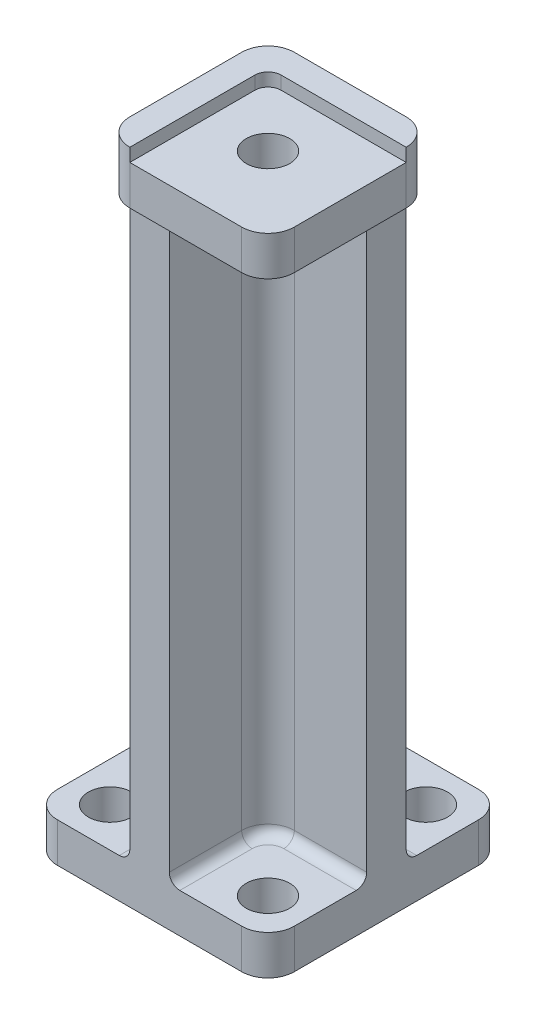
SolidWorks part; units mm, degrees
ref_plane "前视基准面" through (0, 0, 0) normal (0, 0, 1) x (1, 0, 0)
ref_plane "上视基准面" through (0, 0, 0) normal (0, 1, 0) x (1, 0, 0)
ref_plane "右视基准面" through (0, 0, 0) normal (1, 0, 0) x (0, 0, -1)
other "Configuration Table"
sketch "草图1" plane through (0, 0, 0) normal (0, 1, 0) x (1, 0, 0)
  line L1 (-9, 9) -> (9, 9)
  line L2 (-9, 9) -> (-9, -9)
  line L3 (-9, -9) -> (9, -9)
  line L4 (9, 9) -> (9, -9)
  line L5 (-9, 9) -> (9, -9) construction
  line L6 (-9, -9) -> (9, 9) construction
  point P0 (0, 0)
  dimension "D1" = 18
extrude "凸台-拉伸1" add sketch "草图1" along normal blind 3
sketch "草图2" plane through (0, 3, 0) normal (0, 1, 0) x (1, 0, 0)
  line L1 (-6, 6) -> (6, 6) construction
  line L2 (-6, 6) -> (-6, -6) construction
  line L3 (-6, -6) -> (6, -6) construction
  line L4 (6, 6) -> (6, -6) construction
  line L5 (-6, 6) -> (6, -6) construction
  line L6 (-6, -6) -> (6, 6) construction
  circle A0 centre (-6, 6) radius 1.65
  circle A1 centre (6, 6) radius 1.65
  circle A2 centre (6, -6) radius 1.65
  circle A3 centre (-6, -6) radius 1.65
  point P0 (0, 0)
  point P16 (0, 0)
  dimension "D2" = 3.3
  dimension "D1" = 12
  dimension "D3" = 4
extrude "切除-拉伸1" cut sketch "草图2" against normal blind 3
sketch "草图3" plane through (0, 3, 0) normal (0, 1, 0) x (1, 0, 0)
  line L0 (-9, -9) -> (9, -9) construction
  line L1 (-1.5, -9) -> (1.5, -9)
  line L2 (-1.5, -9) -> (-1.5, 1.5)
  line L3 (-1.5, 1.5) -> (1.5, 1.5)
  line L4 (1.5, -9) -> (1.5, 1.5)
  line L5 (9, -9) -> (9, 9) construction
  line L6 (9, -1.5) -> (-1.5, -1.5)
  line L7 (9, -1.5) -> (9, 1.5)
  line L8 (9, 1.5) -> (-1.5, 1.5)
  line L9 (-1.5, -1.5) -> (-1.5, 1.5)
  line L10 (0, 9) -> (0, -9) construction
  line L12 (9, 9) -> (-9, 9) construction
  line L13 (9, 0) -> (-9, 0) construction
  line L14 (-9, 9) -> (-9, -9) construction
  line M16 (9, -9) -> (9, 9)
  line M19 (-9, -9) -> (9, -9)
  dimension "D1" = 3
extrude "凸台-拉伸2" add sketch "草图3" along normal blind 45 contours L6 L4 L3 L2 | L8 L4 L6 M16 | L4 L6 L2 M19
sketch "草图4" plane through (0, 48, 0) normal (0, 1, 0) x (1, 0, 0)
  line L0 (-9, -9) -> (-1.5, -9) construction
  line L1 (-1.5, 1.5) -> (11, 1.5)
  line L2 (-1.5, 1.5) -> (-1.5, -11)
  line L3 (-1.5, -11) -> (11, -11)
  line L4 (11, 1.5) -> (11, -11)
  dimension "D1" = 2
extrude "凸台-拉伸3" add sketch "草图4" along normal blind 3
sketch "草图5" plane through (0, 51, 0) normal (0, 1, 0) x (1, 0, 0)
  line L0 (-1.5, 1.5) -> (-1.5, -11) construction
  line L1 (11, 1.5) -> (-1.5, 1.5) construction
  circle A0 centre (5, -5) radius 1.65
  dimension "D3" = 3.3
  dimension "D1" = 6.5
  dimension "D2" = 6.5
extrude "切除-拉伸2" cut sketch "草图5" against normal blind 3
sketch "草图6" plane through (0, 3, 0) normal (0, 1, 0) x (1, 0, 0)
  line L0 (-9, 9) -> (-9, 0.3299)
  line L1 (-9, 0.3299) -> (-0.9748, 9)
  line L2 (9, 9) -> (-9, 9) construction
  line L3 (-0.9748, 9) -> (-9, 9)
  circle A0 centre (-6, 6) radius 1.65 construction
extrude "切除-拉伸3" cut sketch "草图6" against normal blind 3
fillet "圆角1" radius 2 8 edges at (-9, 1.5, 9) (9, 1.5, 9) (9, 1.5, -9) (-1.5, 49.5, 11) (11, 49.5, 11) (11, 49.5, -1.5) (1.5, 25.5, 1.5) (-1.5, 27, -1.5)
fillet "圆角2" radius 0.8 6 edges at (6.25, 3, 1.5) (2.0858, 3, 2.0858) (4.75, 3, -1.5) (-0.9142, 3, -0.9142) (1.5, 3, 6.25) (-1.5, 3, 4.75)
sketch "草图7" plane through (0, 51, 0) normal (0, 1, 0) x (1, 0, 0)
  line L0 (0.5, -0.5) -> (0.5, -11)
  line L1 (0.5, -0.5) -> (11, -0.5)
  line L4 (-1.5, -0.5) -> (-1.5, -9)
  line L5 (0.5, -11) -> (9, -11)
  line L6 (11, -9) -> (11, -0.5)
  line L7 (9, 1.5) -> (0.5, 1.5)
  line L8 (-1.5, -0.5) -> (-1.5, -9)
  line L9 (0.5, -11) -> (9, -11)
  line L10 (11, -9) -> (11, -0.5)
  line L11 (9, 1.5) -> (0.5, 1.5)
  arc A4 (-1.5, -9) -> (0.5, -11) centre (0.5, -9) ccw
  arc A5 (9, -11) -> (11, -9) centre (9, -9) ccw
  arc A6 (11, -0.5) -> (9, 1.5) centre (9, -0.5) ccw
  arc A7 (0.5, 1.5) -> (-1.5, -0.5) centre (0.5, -0.5) ccw
  arc A8 (-1.5, -9) -> (0.5, -11) centre (0.5, -9) ccw
  arc A9 (9, -11) -> (11, -9) centre (9, -9) ccw
  arc A10 (11, -0.5) -> (9, 1.5) centre (9, -0.5) ccw
  arc A11 (0.5, 1.5) -> (-1.5, -0.5) centre (0.5, -0.5) ccw
  dimension "D1" = 0
extrude "凸台-拉伸4" add sketch "草图7" along normal blind 1
fillet "圆角3" radius 1 1 edges at (0.5, 51.5, 0.5)
